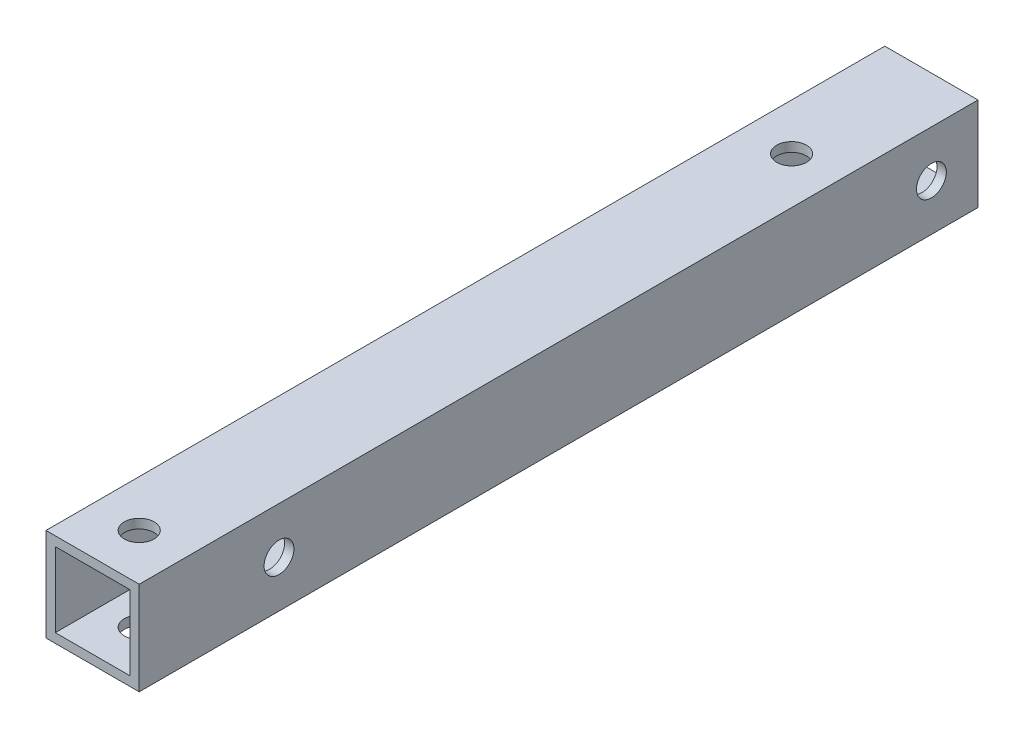
SolidWorks part; units mm, degrees
ref_plane "正面" through (0, 0, 0) normal (0, 0, 1) x (1, 0, 0)
ref_plane "平面" through (0, 0, 0) normal (0, 1, 0) x (1, 0, 0)
ref_plane "右側面" through (0, 0, 0) normal (1, 0, 0) x (0, 0, -1)
sketch "ｽｹｯﾁ1" plane through (0, 0, 0) normal (0, 0, 1) x (1, 0, 0)
  line L0 (4, 4) -> (4, -4)
  line L1 (-5, 5) -> (5, 5)
  line L2 (-5, 5) -> (-5, -5)
  line L3 (-5, -5) -> (5, -5)
  line L4 (5, 5) -> (5, -5)
  line L5 (-5, 5) -> (5, -5) construction
  line L6 (-5, -5) -> (5, 5) construction
  line L7 (-4, -4) -> (4, -4)
  line L8 (-4, 4) -> (-4, -4)
  line L9 (-4, 4) -> (4, 4)
  point P0 (0, 0)
  dimension "D1" = 10
  dimension "D2" = 10
  dimension "D3" = 1
extrude "ﾎﾞｽ - 押し出し1" add sketch "ｽｹｯﾁ1" along normal blind 90
sketch "ｽｹｯﾁ2" plane through (5, 0, 0) normal (1, 0, 0) x (0, 0, -1)
  line L0 (5.5, 0) -> (-5.5, 0) construction
  line L1 (-90, -5) -> (-90, 5) construction
  line L2 (0, 5.5) -> (0, -5.5) construction
  circle A0 centre (-75, 0) radius 1.6
  circle A1 centre (-5, 0) radius 1.6
  dimension "D1" = 3.2
  dimension "D2" = 3.2
  dimension "D4" = 5
  dimension "D3" = 15
extrude "ｶｯﾄ - 押し出し1" cut sketch "ｽｹｯﾁ2" against normal through all
sketch "ｽｹｯﾁ3" plane through (0, 5, 0) normal (0, 1, 0) x (1, 0, 0)
  line L0 (0, -5.5) -> (0, 5.5) construction
  line L1 (-5.5, 0) -> (5.5, 0) construction
  line L2 (5, -90) -> (-5, -90) construction
  circle A0 centre (0, -15) radius 1.6
  circle A1 centre (0, -85) radius 1.6
  dimension "D1" = 3.2
  dimension "D2" = 3.2
  dimension "D3" = 15
  dimension "D4" = 5
extrude "ｶｯﾄ - 押し出し2" cut sketch "ｽｹｯﾁ3" against normal through all
